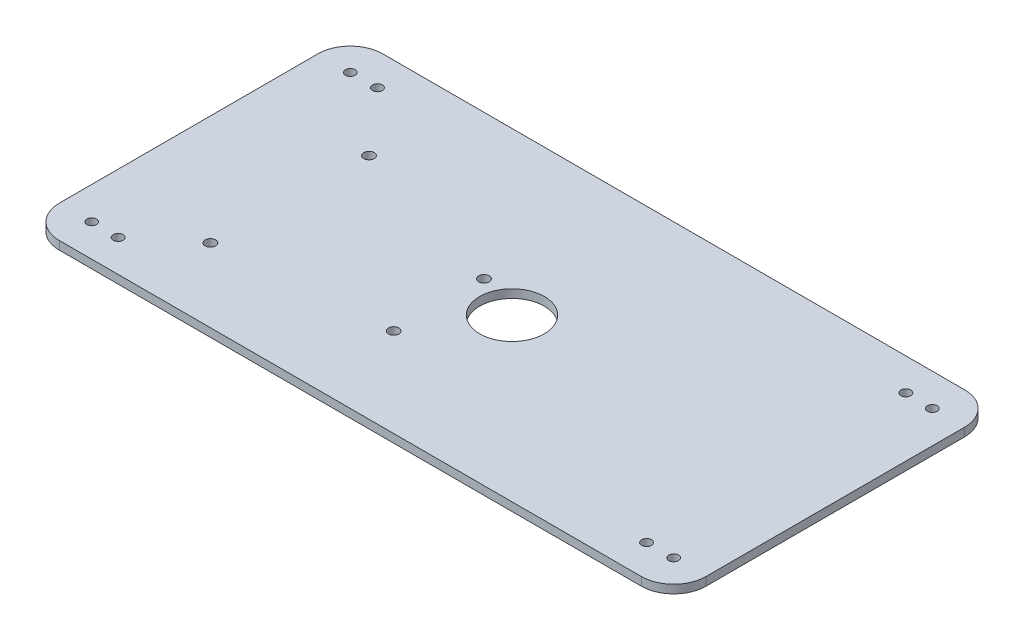
SolidWorks part; units mm, degrees
ref_plane "Front Plane" through (0, 0, 0) normal (0, 0, 1) x (1, 0, 0)
ref_plane "Top Plane" through (0, 0, 0) normal (0, 1, 0) x (1, 0, 0)
ref_plane "Right Plane" through (0, 0, 0) normal (1, 0, 0) x (0, 0, -1)
sketch "Sketch1" plane through (0, 0, 0) normal (0, 1, 0) x (1, 0, 0)
  line L1 (0, 0) -> (200, 0)
  line L2 (0, 0) -> (0, -100)
  line L3 (0, -100) -> (200, -100)
  line L4 (200, 0) -> (200, -100)
  dimension "D1" = 100
  dimension "D2" = 200
extrude "Boss-Extrude1" add sketch "Sketch1" along normal blind 2.6 contours L1 L4 L3 L2
fillet "Fillet1" radius 10 4 edges at (0, 1.3, 0) (0, 1.3, 100) (200, 1.3, 100) (200, 1.3, 0)
sketch "Sketch6" plane through (0, 0, 0) normal (0, -1, 0) x (1, 0, 0)
  line L0 (200, 10) -> (200, 90) construction
  line L1 (10, 0) -> (190, 0) construction
  circle A0 centre (190, 10) radius 1.5
  dimension "D1" = 3
  dimension "D2" = 10
  dimension "D3" = 10
ref_plane "Plane1" through (100, 0, 0) normal (1, 0, 0) x (0, 0, -1)
extrude "Cut-Extrude6" cut sketch "Sketch6" against normal blind 2.6 contours A0
ref_plane "Plane14" through (0, 0, 50) normal (0, 0, 1) x (1, 0, 0)
mirror "Mirror5" about plane through (100, 0, 0) normal (1, 0, 0) of "Cut-Extrude6"
mirror "Mirror6" about plane through (0, 0, 50) normal (0, 0, 1) of "Mirror5", "Cut-Extrude6"
sketch "Sketch15" plane through (0, 0, 0) normal (0, -1, 0) x (1, 0, 0)
  line L0 (100, 0) -> (100, 100) construction
  line L2 (0, 50) -> (200, 50) construction
  line L4 (0, 10) -> (0, 90) construction
  line L5 (200, 10) -> (200, 90) construction
  line L6 (10, 0) -> (190, 0) construction
  line L7 (10, 100) -> (190, 100) construction
  circle A0 centre (100, 50) radius 10
  dimension "D1" = 20
sketch "Sketch16" plane through (0, 2.6, 0) normal (0, 1, 0) x (1, 0, 0)
  circle A0 centre (35.1575, -29.3715) radius 1.6192
extrude "Cut-Extrude9" cut sketch "Sketch16" against normal blind 10
sketch "Sketch17" plane through (0, 2.6, 0) normal (0, 1, 0) x (1, 0, 0)
  circle A0 centre (85.9447, -44.6115) radius 1.6193
extrude "Cut-Extrude10" cut sketch "Sketch17" against normal through all
sketch "Sketch18" plane through (0, 2.6, 0) normal (0, 1, 0) x (1, 0, 0)
  circle A0 centre (34.0145, -77.2886) radius 1.6193
extrude "Cut-Extrude11" cut sketch "Sketch18" against normal through all
sketch "Sketch19" plane through (0, 2.6, 0) normal (0, 1, 0) x (1, 0, 0)
  circle A0 centre (85.9447, -72.5387) radius 1.6193
extrude "Cut-Extrude12" cut sketch "Sketch19" against normal through all
extrude "Cut-Extrude14" cut sketch "Sketch15" against normal through all contours A0
sketch "Sketch23" plane through (0, 2.6, 0) normal (0, 1, 0) x (1, 0, 0)
  circle A0 centre (18.288, -9.906) radius 1.524
extrude "Cut-Extrude15" cut sketch "Sketch23" against normal blind 2.6
mirror "Mirror7" about plane through (100, 0, 0) normal (1, 0, 0) of "Cut-Extrude15"
mirror "Mirror8" about plane through (0, 0, 50) normal (0, 0, 1) of "Mirror7", "Cut-Extrude15"
